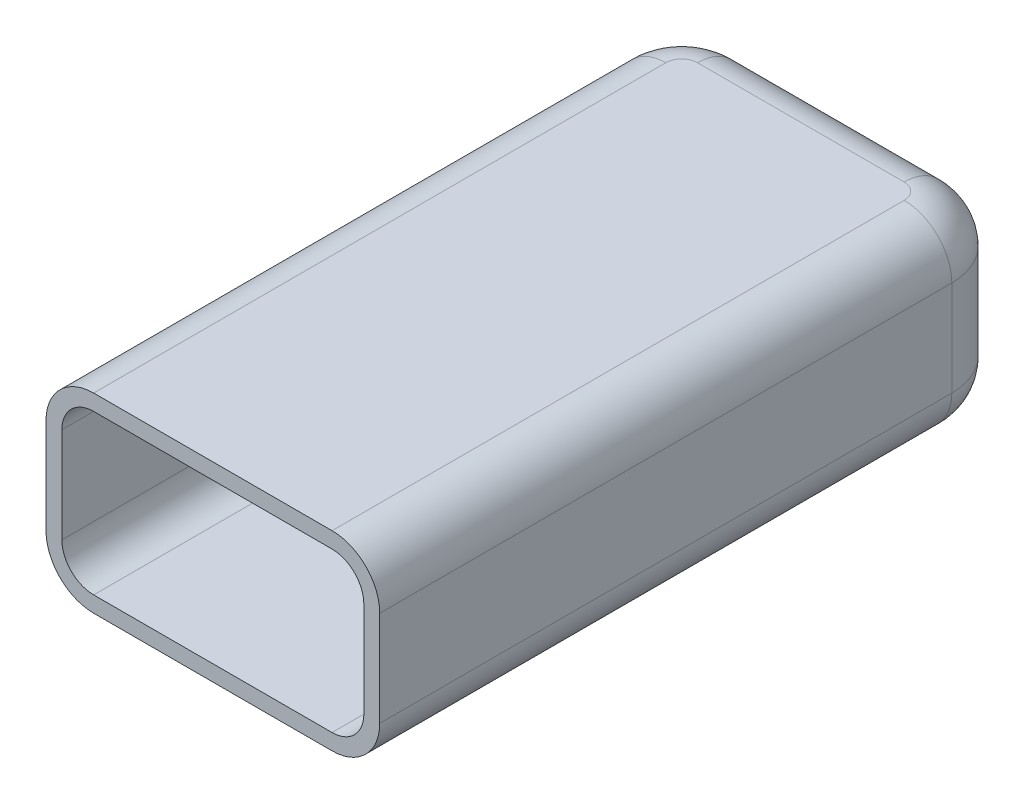
SolidWorks part; units mm, degrees
ref_plane "Front Plane" through (0, 0, 0) normal (0, 0, 1) x (1, 0, 0)
ref_plane "Top Plane" through (0, 0, 0) normal (0, 1, 0) x (1, 0, 0)
ref_plane "Right Plane" through (0, 0, 0) normal (1, 0, 0) x (0, 0, -1)
sketch "Sketch1" plane through (0, 0, 0) normal (0, 1, 0) x (1, 0, 0)
  line L1 (0, 0) -> (21, 0)
  line L2 (0, 0) -> (0, 40)
  line L3 (0, 40) -> (21, 40)
  line L4 (21, 0) -> (21, 40)
  dimension "D1" = 40
  dimension "D2" = 21
extrude "Boss-Extrude1" add sketch "Sketch1" along normal blind 12
sketch "Sketch2" plane through (0, 0, 0) normal (0, 0, 1) x (1, 0, 0)
  line L8 (-10, -10) -> (31, -10)
  line L9 (31, -10) -> (31, 22)
  line L10 (31, 22) -> (-10, 22)
  line L11 (-10, 22) -> (-10, -10)
  line L12 (-10, -10) -> (31, -10)
  line L13 (31, -10) -> (31, 22)
  line L14 (31, 22) -> (-10, 22)
  line L15 (-10, 22) -> (-10, -10)
  dimension "D1" = 10
sketch "Sketch4" plane through (0, 0, 0) normal (0, 0, 1) x (1, 0, 0)
  line L8 (1, 1) -> (20, 1)
  line L9 (20, 1) -> (20, 11)
  line L10 (20, 11) -> (1, 11)
  line L11 (1, 11) -> (1, 1)
  line L12 (1, 1) -> (20, 1)
  line L13 (20, 1) -> (20, 11)
  line L14 (20, 11) -> (1, 11)
  line L15 (1, 11) -> (1, 1)
  dimension "D1" = 1
extrude "Cut-Extrude2" cut sketch "Sketch4" against normal blind 35 contours L14 L15 L12 L13
fillet "Fillet5" radius 4 2 edges at (0, 6, -40) (21, 6, -40)
fillet "Fillet6" radius 3 10 edges at (21, 12, -18) (19.8284, 12, -38.8284) (10.5, 12, -40) (1.1716, 12, -38.8284) (0, 12, -18) (0, 0, -18) (1.1716, 0, -38.8284) (10.5, 0, -40) (19.8284, 0, -38.8284) (21, 0, -18)
fillet "Fillet8" radius 2 4 edges at (20, 1, -17.5) (20, 11, -17.5) (1, 11, -17.5) (1, 1, -17.5)
